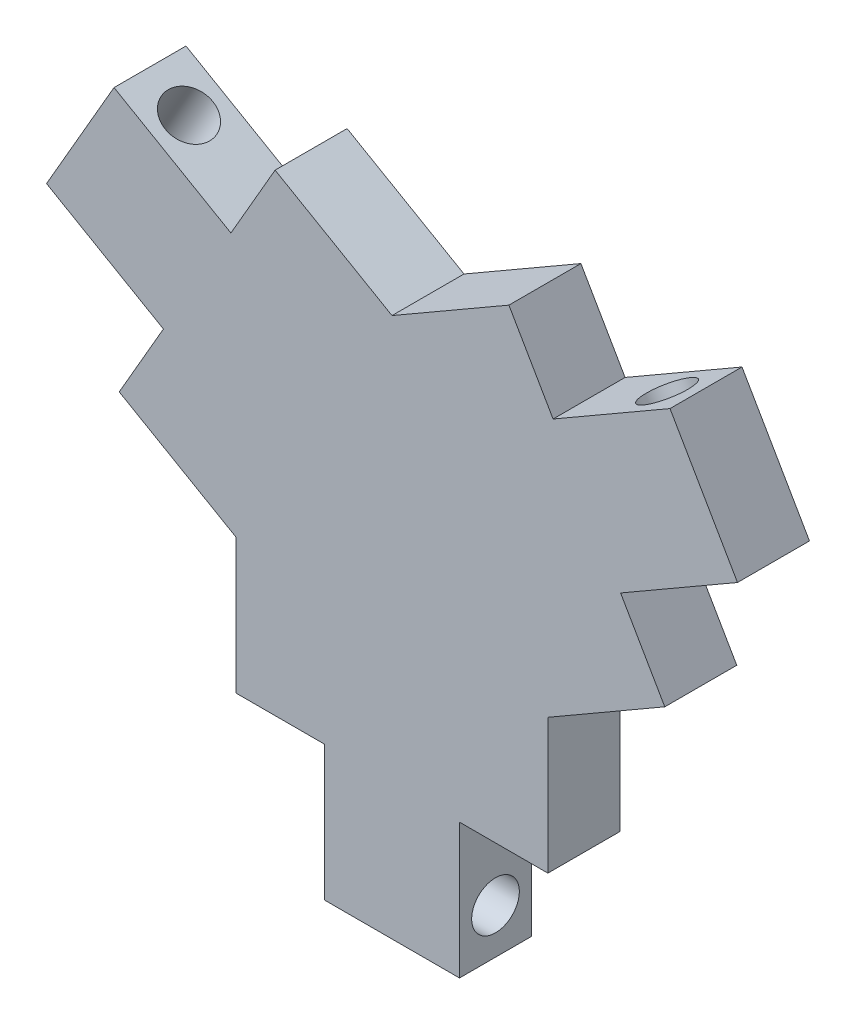
SolidWorks part; units mm, degrees
ref_plane "Front Plane" through (0, 0, 0) normal (1, 0, 0) x (0, 1, 0)
ref_plane "Top Plane" through (0, 0, 0) normal (0, 0, 1) x (0, 1, 0)
ref_plane "Right Plane" through (0, 0, 0) normal (0, 1, 0) x (-1, 0, 0)
sketch "Sketch1" plane through (0, 0, 0) normal (0, 0, 1) x (0, 1, 0)
  line L0 (0, 0) -> (30, 51.9615)
  line L1 (30, 51.9615) -> (60, 0)
  line L2 (60, 0) -> (0, 0)
  line L3 (15, 25.9808) -> (60, 0) construction
  line L4 (45, 25.9808) -> (0, 0) construction
  line L5 (30, 0) -> (30, 51.9615) construction
  line L6 (30, 51.9615) -> (35, 60.6218)
  line L7 (35, 60.6218) -> (65, 43.3013)
  line L8 (65, 43.3013) -> (50, 17.3205)
  line L9 (60, 0) -> (65, -8.6603)
  line L10 (65, -8.6603) -> (35, -25.9808)
  line L11 (35, -25.9808) -> (20, 0)
  line L12 (0, 0) -> (-10, 0)
  line L13 (-10, 0) -> (-10, 34.641)
  line L14 (-10, 34.641) -> (20, 34.641)
  line L15 (50, 51.9615) -> (10.0252, -17.2768) construction
  line L16 (50, -17.3205) -> (11.6287, 49.1406) construction
  line L17 (-10, 17.3205) -> (74.859, 17.3205) construction
  dimension "D1" = 60
  dimension "D2" = 10
extrude "Boss-Extrude5" add sketch "Sketch1" along normal blind 8 contours L8 L7 L6 L1 | L2 L1 L0 | L11 L10 L9 L2 | L14 L13 L12 L0
sketch "Sketch6" plane through (-34.641, 0, 0) normal (-1, 0, 0) x (0, -1, 0)
  line L0 (10, 4) -> (-2.832, 4) construction
  line L1 (10, 8) -> (10, 0) construction
  circle A0 centre (5, 4) radius 2.65
  point P6 (0, 0)
  dimension "D1" = 5.3
  dimension "D2" = 5
extrude "Cut-Extrude4" cut sketch "Sketch6" against normal up to next
sketch "Sketch7" plane through (17.3205, 30, 0) normal (0.5, 0.866, 0) x (-0.866, 0.5, 0)
  line L0 (70, 4) -> (57.1733, 4) construction
  line L1 (70, 8) -> (70, 0) construction
  circle A0 centre (65, 4) radius 2.65
  dimension "D2" = 5.3
  dimension "D1" = 5
extrude "Cut-Extrude5" cut sketch "Sketch7" against normal up to next
sketch "Sketch8" plane through (-8.6603, 15, 0) normal (0.5, -0.866, 0) x (0.866, 0.5, 0)
  line L0 (40, 4) -> (27.2865, 4) construction
  line L1 (40, 8) -> (40, 0) construction
  circle A0 centre (35, 4) radius 2.65
  dimension "D1" = 5.3
  dimension "D2" = 5
extrude "Cut-Extrude6" cut sketch "Sketch8" against normal up to next
sketch "Sketch10" plane through (0, 0, 8) normal (0, 0, 1) x (1, 0, 0)
  line L0 (-34.641, 5) -> (-24.8205, 5)
  line L10 (0, 5) -> (0, -10)
  line L11 (0, -10) -> (-9.8205, -10)
  line L12 (-34.641, -10) -> (-34.641, 5)
  line L13 (-60.6218, 35) -> (-55.7115, 43.5048)
  line L14 (-43.3013, 65) -> (-30.3109, 57.5)
  line L15 (-43.3013, 65) -> (-17.3205, 50) construction
  line L16 (-30.3109, 57.5) -> (-35.2211, 48.9952)
  line L17 (-34.641, 20) -> (-60.6218, 35) construction
  line L18 (-47.6314, 27.5) -> (-60.6218, 35)
  line L19 (8.6603, 65) -> (13.5705, 56.4952)
  line L20 (25.9808, 35) -> (12.9904, 27.5)
  line L21 (25.9808, 35) -> (0, 20) construction
  line L22 (12.9904, 27.5) -> (8.0801, 36.0048)
  line L23 (-17.3205, 50) -> (8.6603, 65) construction
  line L24 (-4.3301, 57.5) -> (8.6603, 65)
  line L25 (-55.7115, 43.5048) -> (-42.7211, 36.0048)
  line L26 (-48.2115, 56.4952) -> (-35.2211, 48.9952)
  line L27 (13.5705, 56.4952) -> (0.5801, 48.9952)
  line L28 (21.0705, 43.5048) -> (8.0801, 36.0048)
  line L29 (-24.8205, 5) -> (-24.8205, -10)
  line L30 (-9.8205, 5) -> (-9.8205, -10)
  line L31 (-42.7211, 36.0048) -> (-47.6314, 27.5)
  line L32 (-48.2115, 56.4952) -> (-43.3013, 65)
  line L33 (-9.8205, 5) -> (0, 5)
  line L34 (-24.8205, -10) -> (-34.641, -10)
  line L35 (0.5801, 48.9952) -> (-4.3301, 57.5)
  line L36 (21.0705, 43.5048) -> (25.9808, 35)
  line L37 (-24.8205, -2.5) -> (-9.8205, -2.5) construction
  line L38 (-41.7163, 52.7452) -> (-49.2163, 39.7548) construction
  line L39 (7.0753, 52.7452) -> (14.5753, 39.7548) construction
  line L40 (8.6603, 65) -> (25.9808, 35) construction
  line L41 (17.3205, 50) -> (-34.641, 20) construction
  line L42 (-51.9615, 50) -> (0, 20) construction
  line L43 (-60.6218, 35) -> (-43.3013, 65) construction
  line L44 (-17.3205, -10) -> (-17.3205, 50) construction
  line L45 (0, -10) -> (-34.641, -10) construction
  point P62 (-17.3205, -2.5)
  point P63 (10.8253, 46.25)
  point P64 (-45.4663, 46.25)
  dimension "D1" = 15
  dimension "D2" = 15
  dimension "D3" = 15
  dimension "D4" = 15
extrude "Cut-Extrude7" cut sketch "Sketch10" against normal up to next
